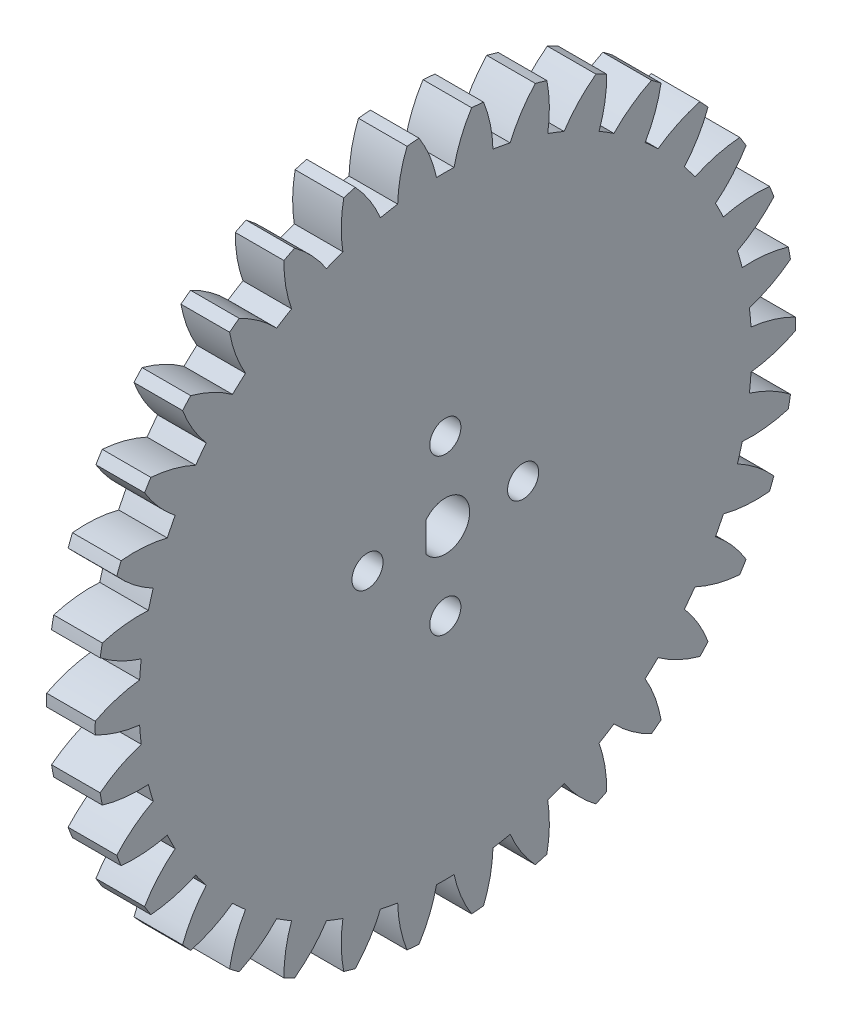
SolidWorks part; units mm, degrees
ref_plane "Plane1" through (0, 0, 0) normal (0, 0, 1) x (1, 0, 0)
ref_plane "Plane2" through (0, 0, 0) normal (0, 1, 0) x (1, 0, 0)
ref_plane "Plane3" through (0, 0, 0) normal (1, 0, 0) x (0, 0, -1)
sketch "HoldingSke" plane through (0, 0, 0) normal (0, 1, 0) x (1, 0, 0)
  line L0 (0, 0) -> (0.4145, -0.2796)
  line L1 (-15, 0) -> (100, 0) construction
  line L2 (0, 0) -> (-2.1039, 2.3779)
  line L3 (0, 0) -> (-11.863, 4.5341)
  line L4 (0, 0) -> (7.1596, 4.8292)
  line L5 (0, 0) -> (-46.8476, -17.4728)
  line L6 (0, 0) -> (-6.6317, -4.4744)
  line L7 (-2.1039, 2.3779) -> (8.6586, 51.2059)
  line L8 (-76.2, 54.61) -> (-76.1, 54.61)
  line L9 (-71.009, 38.7566) -> (-53.1078, 45.2721)
  line L10 (-76.2, 71.12) -> (104.1128, 71.12)
  line L11 (0, 0) -> (-8, 0)
  line L12 (-76.2, 101.6) -> (-76.133, 101.6)
  line L13 (24.9733, 27.94) -> (52.9518, 28.4284)
  line L14 (24.9733, 27.94) -> (24.9743, 27.94)
  line L15 (24.9733, 27.94) -> (100.4006, 29.5858)
  line L16 (-63.627, -2) -> (-12.827, -2)
  circle A0 centre (0, 0) radius 0.4
  circle A1 centre (0, 0) radius 31.499
  circle A2 centre (0, 0) radius 37.5
  circle A3 centre (0, 0) radius 0.4
  dimension "MHD" = 62.998
  dimension "Hub_dia" = 75
  dimension "Bore" = 0.8
  dimension "MBD" = 0.8
  dimension "Num_teeth" = 34
  dimension "Pitch" = 0.5
  dimension "Overall_len" = 50
  dimension "Show_teeth" = 34
  dimension "Thickness" = 8
  dimension "OAL" = 50.0001
  dimension "T_dim" = 0.1
  dimension "Ap" = 20
  dimension "H" = 19.05
  dimension "Pitch_radius" = 180.3128
  dimension "Width" = 8
  dimension "Backlash" = 0.067
  dimension "Addendum_fac" = 1
  dimension "Dedendum_fac" = 1.25
  dimension "Clearance_fac" = 0.25
  dimension "Dedendum_add" = 0.001
  dimension "Module" = 2
sketch "BasProSke" plane through (0, 0, 0) normal (0, 1, 0) x (1, 0, 0)
  line L0 (-10, 0) -> (60, 0) construction
  line L1 (0, 0) -> (0, 36)
  line L2 (0, 0) -> (5, 0)
  line L3 (5, 0) -> (5, 36)
  line L4 (5, 36) -> (0, 36)
  dimension "Thickness" = 5
  dimension "Diameter" = 72
revolve "Base-Revolve" add sketch "BasProSke" angle 360 about L0
sketch "TooCutSke" plane through (0, 0, 0) normal (1, 0, 0) x (0, 0, -1)
  line L1 (0, 0) -> (0, 107) construction
  line L2 (0, 0) -> (-1.6875, 33.9581) construction
  line L3 (0, 0) -> (-6.2685, 67.6481) construction
  line L4 (-1.6875, 33.9581) -> (-3.1343, 33.824) construction
  arc A0 (0.9019, 31.4861) -> (-0.9019, 31.4861) centre (0, 0) ccw
  arc A1 (2.7224, 35.9224) -> (-2.7224, 35.9224) centre (0, 0) ccw
  circle A2 centre (0, 0) radius 34 construction
  circle A3 centre (0, 0) radius 31.9495 construction
  arc A4 (-0.9019, 31.4861) -> (-2.7224, 35.9224) centre (-14.1969, 28.622) ccw
  arc A5 (2.7224, 35.9224) -> (0.9019, 31.4861) centre (14.1969, 28.622) ccw
  dimension "Root_dia" = 62.998
  dimension "Overcut_dia" = 72.0508
  dimension "Pitch_dia" = 68
  dimension "Base_dia" = 63.8991
  dimension "Flank_rad" = 13.6
  dimension "Half_ang" = 5.294
  dimension "Half_CT" = 1.453
extrude "ToothCut" cut sketch "TooCutSke" along normal through all
fillet "Breaks" [suppressed] radius 0.04
fillet "RootFillets" [suppressed] radius 0.501
pattern_circular "TeethCuts" count 34 every 10.588 about axis through (-10, 0, 0) along (1, 0, 0) of "ToothCut", "RootFillets", "Breaks"
sketch "HubNeaOneSke" plane through (0, 0, 0) normal (-1, 0, 0) x (0, 0, 1)
  circle A0 centre (0, 0) radius 31.499
  dimension "Diameter" = 62.998
extrude "HubNearOne" [suppressed] add sketch "HubNeaOneSke" along normal blind 45.0001
sketch "HubNeaBotSke" plane through (0, 0, 0) normal (-1, 0, 0) x (0, 0, 1)
  circle A0 centre (0, 0) radius 31.499
  dimension "Diameter" = 62.998
extrude "HubNearBoth" [suppressed] add sketch "HubNeaBotSke" along normal blind 22.5
ref_plane "FarPln" through (5, 0, 0) normal (1, 0, 0) x (0, 0, -1)
sketch "HubFarSke" plane through (5, 0, 0) normal (1, 0, 0) x (0, 0, -1)
  circle A0 centre (0, 0) radius 31.499
  dimension "Diameter" = 62.998
extrude "HubFar" [suppressed] add sketch "HubFarSke" along normal blind 22.5
sketch "BorSke" plane through (0, 0, 0) normal (1, 0, 0) x (0, 0, -1)
  circle A0 centre (0, 0) radius 0.4
  dimension "Diameter" = 0.8
extrude "Bore" cut sketch "BorSke" along normal mid plane 100.0001
sketch "KeySke" plane through (0, 0, 0) normal (1, 0, 0) x (0, 0, -1)
  line L0 (-0.05, 0) -> (-0.05, 0.5)
  line L1 (-0.05, 0.5) -> (0.05, 0.5)
  line L2 (0.05, 0.5) -> (0.05, 0)
  line L3 (0, 0) -> (0, 34) construction
  line L4 (-0.05, 0) -> (0.05, 0)
  dimension "Offset" = 0.5
  dimension "Width" = 0.1
extrude "Keyway" [suppressed] cut sketch "KeySke" along normal mid plane 100.0001
pattern_circular "Keyway2" [suppressed] count 2 every 90 about axis through (-10, 0, 0) along (1, 0, 0)
sketch "Schizzo1" plane through (5, 0, 0) normal (1, 0, 0) x (0, 0, -1)
  line L0 (-2, 1.5) -> (-2, -1.5)
  arc A0 (-2, -1.5) -> (-2, 1.5) centre (0, 0) ccw
  dimension "D1" = 5
  dimension "D2" = 2
extrude "Taglio-Estrusione1" cut sketch "Schizzo1" against normal blind 10
sketch "Schizzo2" plane through (5, 0, 0) normal (1, 0, 0) x (0, 0, -1)
  circle A0 centre (0, 0) radius 8 construction
  circle A1 centre (0, 8) radius 1.6
  circle A2 centre (8, 0) radius 1.6
  circle A3 centre (0, -8) radius 1.6
  circle A4 centre (-8, 0) radius 1.6
  dimension "D1" = 16
  dimension "D2" = 3.2
extrude "Taglio-Estrusione2" cut sketch "Schizzo2" against normal blind 10
equation "' \"Module@HoldingSke\" = 6.35"
equation "' \"Num_teeth@HoldingSke\" = 12"
equation "' \"Ap@HoldingSke\" =  20"
equation "' \"Ap@HoldingSke\" = 20"
equation "' \"Width@HoldingSke\" = 0.5 * 25.4"
equation "' \"Hub_dia@HoldingSke\"= 1 * 25.4"
equation "' \"Hub_dia@HoldingSke\" = 1 * 25.4"
equation "' \"Overall_len@HoldingSke\" = 1.0 * 25.4"
equation "' \"Bore@HoldingSke\" = 0.75 * 25.4"
equation "' \"T_dim@HoldingSke\" = 0.1 * 25.4"
equation "' \"Width@KeySke\" = 0.25 * 25.4"
equation "' \"Show_teeth@HoldingSke\" = 13"
equation "' \"Backlash@HoldingSke\" = 0.009 * 25.4"
equation "' \"Addendum_fac@HoldingSke\" = 1.0"
equation "' \"Dedendum_fac@HoldingSke\" = 1.25"
equation "' \"Dedendum_add@HoldingSke\" = 0.00005 * 25.4"
equation "' \"Clearance_fac@HoldingSke\" = 0.25"
equation "\"Pitch@HoldingSke\" = 1 / \"Module@HoldingSke\""
equation "\"Overcut_dia@TooCutSke\" = (\"Num_teeth@HoldingSke\" + 2 * \"Addendum_fac@HoldingSke\") / \"Pitch@HoldingSke\" + 0.002 * 25.4"
equation "\"Pitch_dia@TooCutSke\" = \"Num_teeth@HoldingSke\" / \"Pitch@HoldingSke\""
equation "\"Base_dia@TooCutSke\" = \"Num_teeth@HoldingSke\" / \"Pitch@HoldingSke\" * cos((\"Ap@HoldingSke\"  * 3.14159265 / 180))"
equation "\"Root_dia@TooCutSke\" = (\"Num_teeth@HoldingSke\" + 2) / \"Pitch@HoldingSke\" - 2 * (\"Addendum_fac@HoldingSke\" + \"Dedendum_fac@HoldingSke\") / \"Pitch@HoldingSke\" - \"Dedendum_add@HoldingSke\" * 2"
equation "\"Half_ang@TooCutSke\" = 180 / \"Num_teeth@HoldingSke\""
equation "\"Half_CT@TooCutSke\" = \"Num_teeth@HoldingSke\" / \"Pitch@HoldingSke\" * sin((3.14159265 / 2 / \"Num_teeth@HoldingSke\")) / 2 - 7 * \"Backlash@HoldingSke\" / 4"
equation "\"Flank_rad@TooCutSke\" = \"Num_teeth@HoldingSke\" / \"Pitch@HoldingSke\" / 5"
equation "\"Radius@RootFillets\" = \"Clearance_fac@HoldingSke\" / \"Pitch@HoldingSke\" + \"Dedendum_add@HoldingSke\""
equation "\"Break_rad@Breaks\" = 0.02 / \"Pitch@HoldingSke\""
equation "\"Thickness@HoldingSke\" = \"Width@HoldingSke\""
equation "\"OAL@HoldingSke\" = \"Thickness@HoldingSke\""
equation "\"MHD@HoldingSke\" = (\"Num_teeth@HoldingSke\" + 2) / \"Pitch@HoldingSke\" - 2 * (\"Addendum_fac@HoldingSke\" + \"Dedendum_fac@HoldingSke\")  / \"Pitch@HoldingSke\" - \"Dedendum_add@HoldingSke\" * 2"
equation "\"MBD@HoldingSke\" = (\"Num_teeth@HoldingSke\" + 2) / \"Pitch@HoldingSke\" - 2 * (\"Addendum_fac@HoldingSke\" + \"Dedendum_fac@HoldingSke\")  / \"Pitch@HoldingSke\" - \"Dedendum_add@HoldingSke\" * 2 - 0.002 * 25.4"
equation "\"MHD@HoldingSke\" = ((sgn( \"MHD@HoldingSke\" - \"Hub_dia@HoldingSke\" )-1)*( \"MHD@HoldingSke\" - \"Hub_dia@HoldingSke\" ))/-2+ \"Hub_dia@HoldingSke\""
equation "\"MBD@HoldingSke\" = ((sgn( \"MBD@HoldingSke\" - \"Bore@HoldingSke\" )-1)*( \"MBD@HoldingSke\" - \"Bore@HoldingSke\" ))/-2+ \"Bore@HoldingSke\""
equation "\"OAL@HoldingSke\" = ((sgn( \"OAL@HoldingSke\" - \"Overall_len@HoldingSke\" )+1)*( \"OAL@HoldingSke\" - \"Overall_len@HoldingSke\" ))/2 + \"Overall_len@HoldingSke\" + 0.000002 * 25.4"
equation "\"Num_teeth@TeethCuts\" = int( \"Show_teeth@HoldingSke\" ) + 1"
equation "\"Num_teeth@TeethCuts\" = ((sgn( \"Num_teeth@TeethCuts\" - \"Num_teeth@HoldingSke\" )-1)*( \"Num_teeth@TeethCuts\" - \"Num_teeth@HoldingSke\" ))/-2+ \"Num_teeth@HoldingSke\""
equation "\"Num_teeth@TeethCuts\" = ((sgn( \"Num_teeth@TeethCuts\" - 2.0)+1)*( \"Num_teeth@TeethCuts\" - 2.0))/2 +2.0"
equation "\"Angle@TeethCuts\" = 360.0 / \"Num_teeth@HoldingSke\""
equation "\"Diameter@BasProSke\" = (\"Num_teeth@HoldingSke\" + 2 * \"Addendum_fac@HoldingSke\") / \"Pitch@HoldingSke\""
equation "\"Thickness@BasProSke\"=5"
equation "' \"Fillet_rad@BasProSke\" =  \"Thickness@HoldingSke\" * 0.05"
equation "' \"Fillet_rad@BasProSke\" = \"Thickness@HoldingSke\" * 0.05"
equation "\"MHD@HoldingSke\" = ((sgn( \"MHD@HoldingSke\" - \"Root_dia@TooCutSke\" )-1)*( \"MHD@HoldingSke\" - \"Root_dia@TooCutSke\" ))/-2+ \"Root_dia@TooCutSke\""
equation "\"Diameter@HubNeaOneSke\" = \"MHD@HoldingSke\""
equation "\"Length@HubNearOne\" = \"OAL@HoldingSke\" - \"Thickness@BasProSke\""
equation "\"Diameter@HubNeaBotSke\" = \"MHD@HoldingSke\""
equation "\"Length@HubNearBoth\" = ( \"OAL@HoldingSke\" - \"Thickness@BasProSke\" ) / 2.0"
equation "\"Thickness@FarPln\" = \"Thickness@BasProSke\""
equation "\"Diameter@HubFarSke\" = \"MHD@HoldingSke\""
equation "\"Length@HubFar\" = ( \"OAL@HoldingSke\" - \"Thickness@BasProSke\" ) / 2.0"
equation "\"Diameter@BorSke\" = \"MBD@HoldingSke\""
equation "\"D1@Bore\" = \"OAL@HoldingSke\" * 2.0"
equation "\"D1@Keyway\" = \"OAL@HoldingSke\" * 2.0"
equation "\"Offset@KeySke\" = \"T_dim@HoldingSke\" + \"MBD@HoldingSke\" / 2.0"
